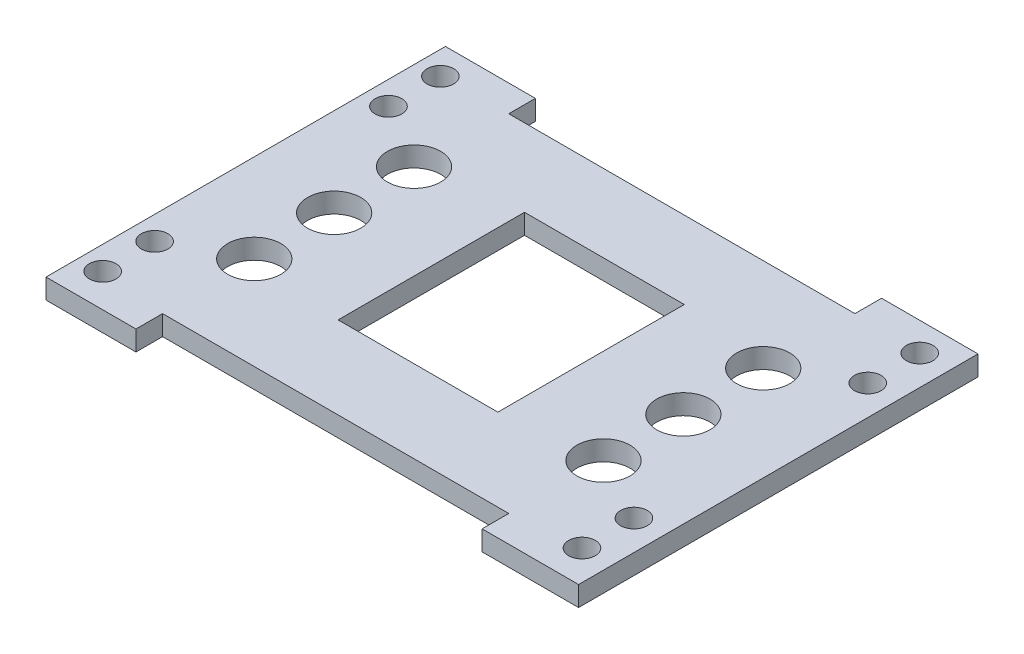
SolidWorks part; units mm, degrees
ref_plane "Front Plane" through (0, 0, 0) normal (0, 0, 1) x (1, 0, 0)
ref_plane "Top Plane" through (0, 0, 0) normal (0, 1, 0) x (1, 0, 0)
ref_plane "Right Plane" through (0, 0, 0) normal (1, 0, 0) x (0, 0, -1)
sketch "Top Plate 2 Sketch" plane through (0, 0, 0) normal (0, 1, 0) x (1, 0, 0)
  line L0 (0, -30.0856) -> (0, 33.2409) construction
  line L1 (-19.7564, 14.8173) -> (20.2436, 14.8173)
  line L2 (-19.7564, 14.8173) -> (-19.7564, -15.1827)
  line L3 (-19.7564, -15.1827) -> (20.2436, -15.1827)
  line L4 (20.2436, 14.8173) -> (20.2436, -15.1827)
  line L5 (-19.7564, 14.8173) -> (20.2436, -15.1827) construction
  line L6 (-19.7564, -15.1827) -> (20.2436, 14.8173) construction
  line L7 (-6, 7) -> (6, 7)
  line L8 (-6, 7) -> (-6, -7)
  line L9 (-6, -7) -> (6, -7)
  line L10 (6, 7) -> (6, -7)
  line L11 (-6, 7) -> (6, -7) construction
  line L12 (-6, -7) -> (6, 7) construction
  line L13 (-43.2411, 0) -> (40.5801, 0) construction
  line L14 (-13, 12.8173) -> (13, 12.8173)
  line L15 (-13, -15.1827) -> (13, -15.1827)
  line L16 (-13, -15.1827) -> (-13, -13.1827)
  line L17 (-13, -13.1827) -> (13, -13.1827)
  line L18 (13, -15.1827) -> (13, -13.1827)
  line L19 (13, 14.8173) -> (13, 12.8173)
  line L20 (-13, 14.8173) -> (13, 14.8173)
  line L21 (-13, 14.8173) -> (-13, 12.8173)
  circle A0 centre (-13.1133, 5.8173) radius 2
  circle A1 centre (-13.1133, -0.1827) radius 2
  circle A2 centre (-13.1133, -6.1827) radius 2
  circle A3 centre (-18, -12.6827) radius 1
  circle A4 centre (-18, -8.7827) radius 1
  circle A5 centre (-18, 12.6827) radius 1
  circle A6 centre (-18, 8.7827) radius 1
  circle A7 centre (18, -12.6827) radius 1
  circle A8 centre (18, -8.7827) radius 1
  circle A9 centre (18, 8.7827) radius 1
  circle A10 centre (18, 12.6827) radius 1
  circle A11 centre (13.1133, -6.1827) radius 2
  circle A12 centre (13.1133, -0.1827) radius 2
  circle A13 centre (13.1133, 5.8173) radius 2
  point P0 (0, 0)
  point P6 (2.0593, -2.9996)
  dimension "D5" = 4
  dimension "D6" = 4
  dimension "D7" = 4
  dimension "D8" = 15
  dimension "D9" = 6.1827
  dimension "D10" = 2
  dimension "D12" = 2
  dimension "D13" = 3.9
  dimension "D14" = 18
  dimension "D18" = 9
  dimension "D19" = 9
  dimension "D2" = 30
  dimension "D3" = 12
  dimension "D4" = 14
  dimension "D11" = 2.5
  dimension "D15" = 2
  dimension "D16" = 26
  dimension "D17" = 13
  dimension "D20" = 40
  dimension "D21" = 26
  dimension "D22" = 2
  dimension "D23" = 13
  dimension "D24" = 6
extrude "Top Plate 2" add sketch "Top Plate 2 Sketch" along normal blind 1.5 contours L21 L1 L2 L3 L16 L17 L18 L4 L19 L14 A12 A8 A6 L7 L10 L9 L8 A0 A1 A2 A3 A4 A5 A7 A9 A10 A11 A13
